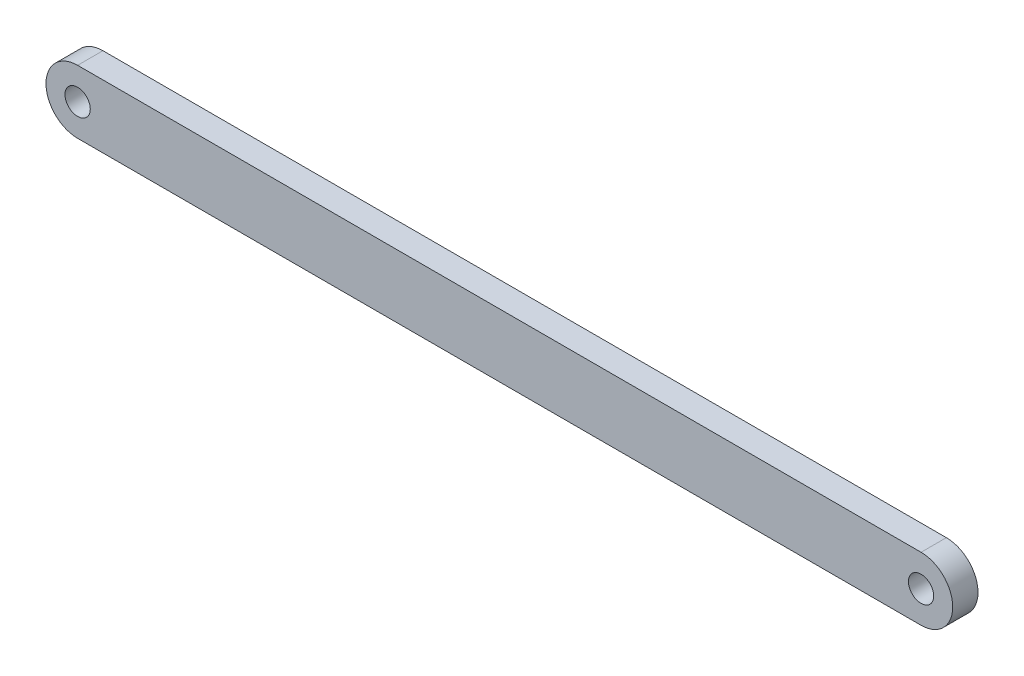
SolidWorks part; units mm, degrees
ref_plane "Front Plane" through (0, 0, 0) normal (0, 0, 1) x (1, 0, 0)
ref_plane "Top Plane" through (0, 0, 0) normal (0, 1, 0) x (1, 0, 0)
ref_plane "Right Plane" through (0, 0, 0) normal (1, 0, 0) x (0, 0, -1)
sketch "Sketch2" plane through (0, 0, 0) normal (0, 0, 1) x (1, 0, 0)
  line L0 (0, -3.75) -> (100, -3.75)
  line L1 (100, 3.75) -> (0, 3.75)
  circle A0 centre (0, 0) radius 3.75
  circle A1 centre (100, 0) radius 3.75
  circle A2 centre (0, 0) radius 1.5
  circle A3 centre (100, 0) radius 1.5
  dimension "D1" = 7.5
  dimension "D2" = 3
  dimension "D3" = 3
  dimension "D4" = 100
extrude "Boss-Extrude1" add sketch "Sketch2" along normal blind 3 contours A0 A2 | A1 L1 A0 L0 | A1 A3
